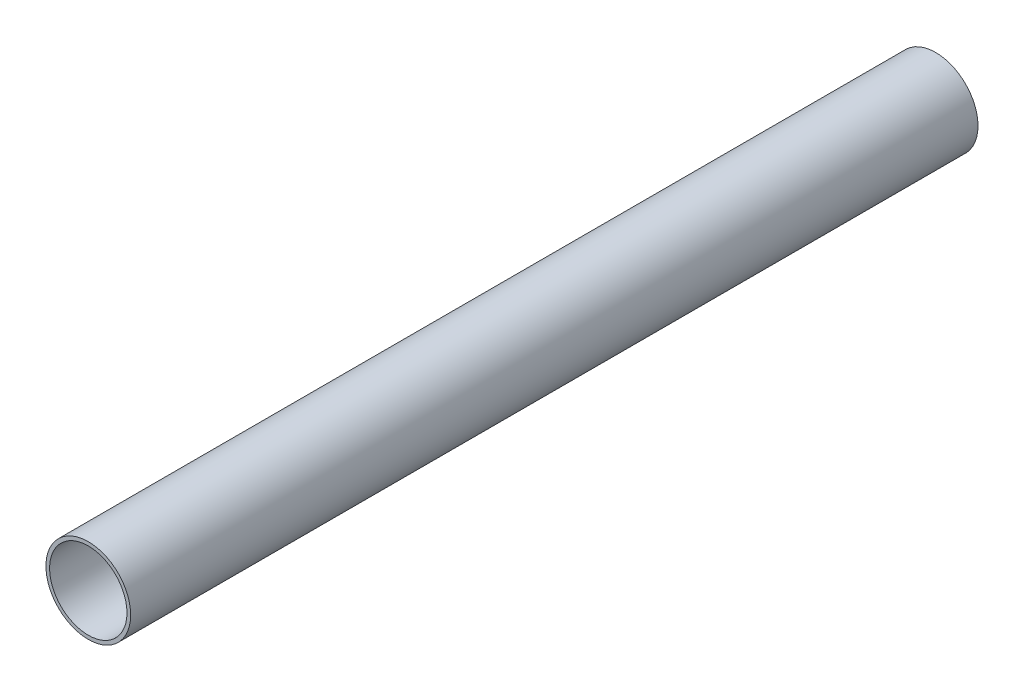
SolidWorks part; units mm, degrees
ref_plane "Front Plane" through (0, 0, 0) normal (0, 0, 1) x (1, 0, 0)
ref_plane "Top Plane" through (0, 0, 0) normal (0, 1, 0) x (1, 0, 0)
ref_plane "Right Plane" through (0, 0, 0) normal (1, 0, 0) x (0, 0, -1)
sketch "Sketch1" plane through (0, 0, 0) normal (0, 0, 1) x (1, 0, 0)
  circle A0 centre (0, 0) radius 11.5
  circle A1 centre (0, 0) radius 10.5
  dimension "D1" = 23
  dimension "D2" = 21
extrude "Boss-Extrude1" add sketch "Sketch1" along normal blind 230
